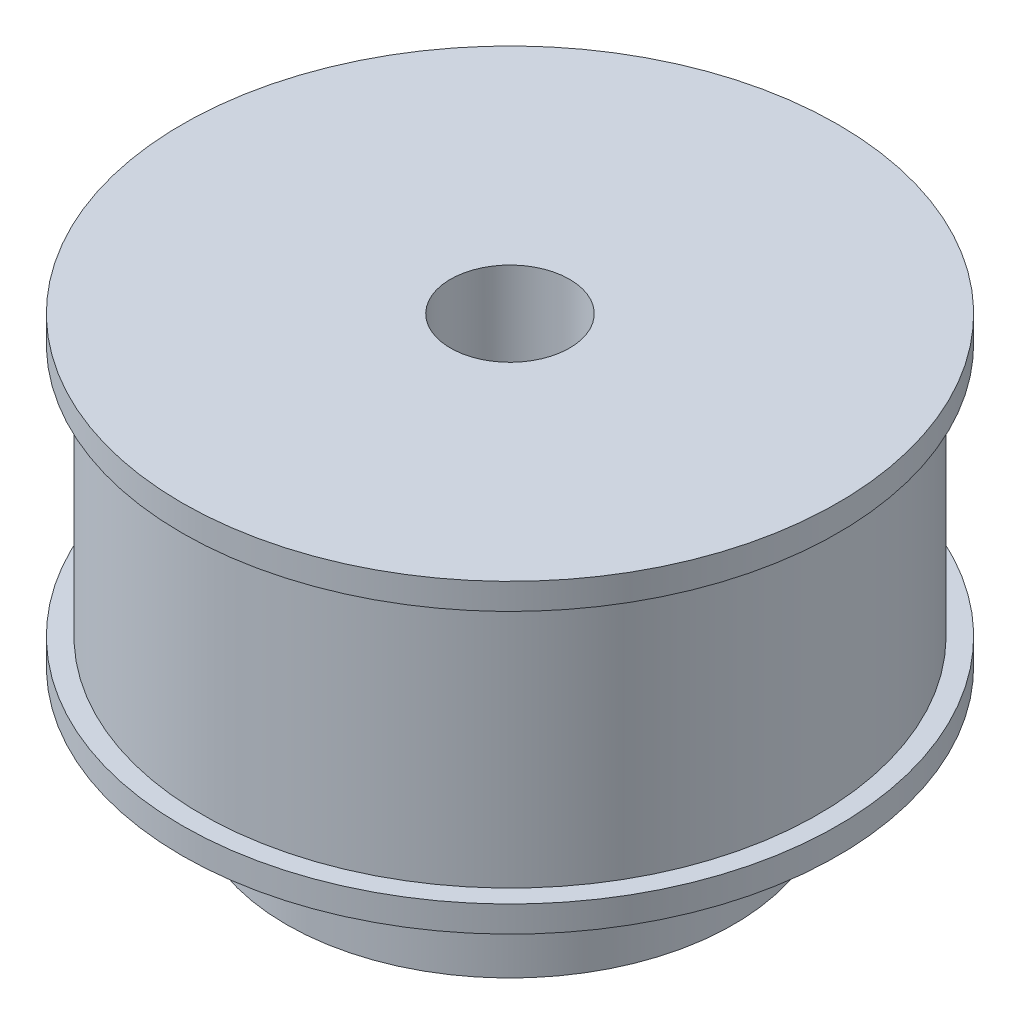
SolidWorks part; units mm, degrees
ref_plane "Front Plane" through (0, 0, 0) normal (0, 0, 1) x (1, 0, 0)
ref_plane "Top Plane" through (0, 0, 0) normal (0, 1, 0) x (1, 0, 0)
ref_plane "Right Plane" through (0, 0, 0) normal (1, 0, 0) x (0, 0, -1)
sketch "Sketch1" plane through (0, 0, 0) normal (0, 0, 1) x (1, 0, 0)
  line L0 (4, 0) -> (15, 0)
  line L1 (15, 0) -> (15, 7.5)
  line L2 (15, 7.5) -> (22, 7.5)
  line L3 (22, 7.5) -> (22, 9.25)
  line L4 (22, 9.25) -> (20.69, 9.25)
  line L5 (20.69, 9.25) -> (20.69, 26.25)
  line L6 (20.69, 26.25) -> (22, 26.25)
  line L7 (22, 26.25) -> (22, 28)
  line L8 (22, 28) -> (4, 28)
  line L9 (4, 28) -> (4, 0)
  line L10 (0, 0) -> (0, 38.5) construction
  dimension "D1" = 4
  dimension "D2" = 22
  dimension "D3" = 28
  dimension "D4" = 20.5
  dimension "D5" = 17
  dimension "D6" = 15
  dimension "D7" = 20.69
revolve "Revolve1" add sketch "Sketch1" angle 360 about L10
sketch "Sketch2" [suppressed] plane through (0, 28, 0) normal (0, 1, 0) x (1, 0, 0)
  circle A0 centre (0, 0) radius 5.5
  dimension "D1" = 11
extrude "Cut-Extrude1" [suppressed] cut sketch "Sketch2" against normal blind 33
sketch "Sketch3" [suppressed] plane through (0, 28, 0) normal (0, 1, 0) x (1, 0, 0)
  line L1 (-2, 5.1235) -> (2, 5.1235)
  line L2 (-2, 5.1235) -> (-2, 7.3)
  line L3 (-2, 7.3) -> (2, 7.3)
  line L4 (2, 5.1235) -> (2, 7.3)
  circle A0 centre (0, 0) radius 5.5 construction
  circle A1 centre (0, 0) radius 5.5
  dimension "D1" = 13.3694
  dimension "D2" = 5.9413
extrude "Cut-Extrude2" [suppressed] cut sketch "Sketch3" against normal blind 33
sketch "Sketch4" [suppressed] plane through (0, 0, -7.3) normal (0, 0, 1) x (1, 0, 0)
  line L0 (0, 0) -> (0, 3.75) construction
  line L1 (-15, 0) -> (15, 0) construction
  circle A0 centre (0, 3.75) radius 1.2
  dimension "D2" = 2.4
  dimension "D1" = 3.75
extrude "Cut-Extrude3" [suppressed] cut sketch "Sketch4" against normal blind 80
sketch "Sketch5" plane through (0, 0, 0) normal (0, 0, 1) x (1, 0, 0)
  line L0 (-15, 0) -> (15, 0) construction
  line L1 (-15, 0) -> (-15, 7.5) construction
  line L2 (-15, 7.5) -> (15, 7.5) construction
  circle A0 centre (0, 3.5267) radius 2
  dimension "D1" = 4
  dimension "D2" = 3.5267
  dimension "D3" = 7.5
extrude "Cut-Extrude4" cut sketch "Sketch5" against normal blind 18
sketch "Sketch6" plane through (0, 0, 0) normal (1, 0, 0) x (0, 0, -1)
  line L0 (-15, 0) -> (-15, 7.5) construction
  line L1 (-15, 7.5) -> (15, 7.5) construction
  line L2 (-22, 7.5) -> (22, 7.5) construction
  line L3 (-15, 0) -> (15, 0) construction
  circle A0 centre (0, 3.75) radius 2
  dimension "D1" = 4
  dimension "D2" = 7.5
  dimension "D3" = 3.75
extrude "Cut-Extrude5" cut sketch "Sketch6" against normal blind 18
equation "\"D3@Sketch6\"=\"D2@Sketch6\"/2"
